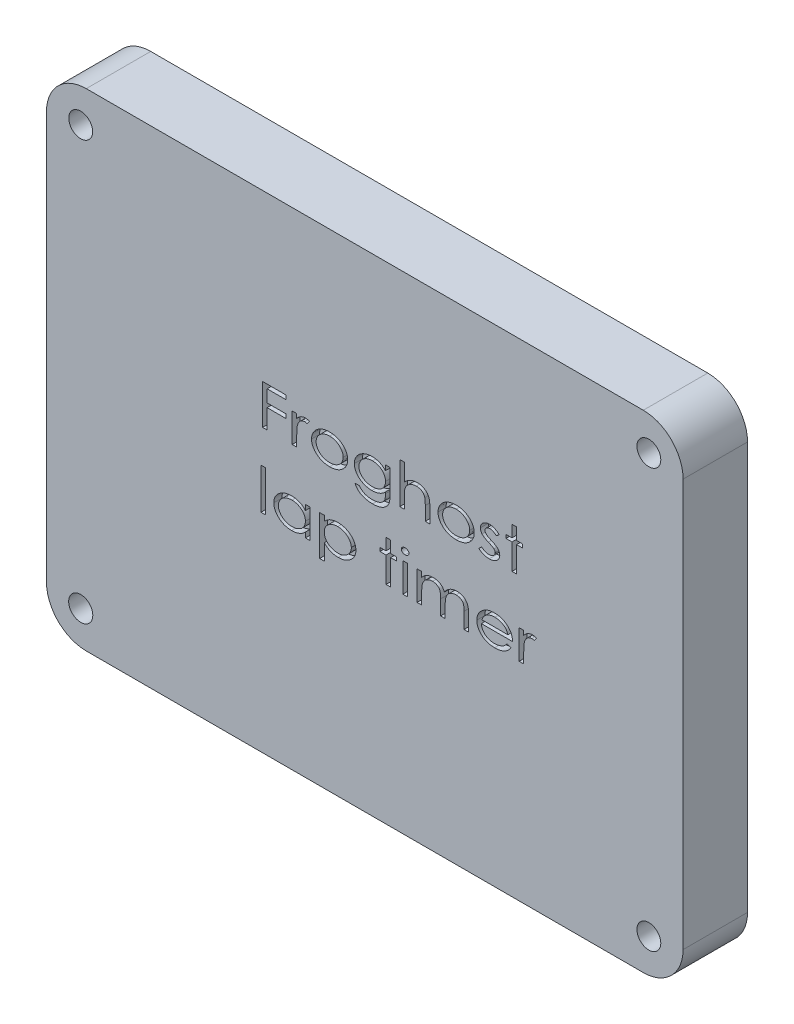
SolidWorks part; units mm, degrees
ref_plane "Plan de face" through (0, 0, 0) normal (0, 0, 1) x (1, 0, 0)
ref_plane "Plan de dessus" through (0, 0, 0) normal (0, 1, 0) x (1, 0, 0)
ref_plane "Plan de droite" through (0, 0, 0) normal (1, 0, 0) x (0, 0, -1)
sketch "Esquisse1" plane through (0, 0, 0) normal (0, 0, 1) x (1, 0, 0)
  line L0 (-22.7007, 21.2079) -> (44.6967, 21.2079)
  line L1 (-28.9007, 23.2079) -> (51.0993, 23.2079)
  line L2 (-28.9007, 23.2079) -> (-28.9007, -37.9921)
  line L3 (-28.9007, -37.9921) -> (51.0993, -37.9921)
  line L4 (51.0993, 23.2079) -> (51.0993, -37.9921)
  line L5 (49.0993, 17.0079) -> (49.0993, -31.7921)
  line L6 (44.8993, -35.9921) -> (-22.7007, -35.9921)
  line L7 (-26.9007, -31.7921) -> (-26.9007, 17.0079)
  arc A0 (-22.7007, 21.2079) -> (-26.9007, 17.0079) centre (-24.6007, 18.9079) cw
  arc A1 (-26.9007, -31.7921) -> (-22.7007, -35.9921) centre (-24.8007, -33.8921) cw
  arc A2 (44.6967, 21.2079) -> (49.0993, 17.0079) centre (46.898, 19.1079) ccw
  arc A3 (49.0993, -31.7921) -> (44.8993, -35.9921) centre (47.0205, -33.9133) ccw
  circle A4 centre (-24.6007, 18.9079) radius 1.5
  circle A6 centre (46.7993, 18.9079) radius 1.5
  circle A7 centre (46.7999, -33.6947) radius 1.4974
  circle A8 centre (-24.5961, -33.7076) radius 1.5162
extrude "Boss.-Extru.1" add sketch "Esquisse1" along normal blind 6.1
sketch "Esquisse2" plane through (0, 0, 6.1) normal (0, 0, 1) x (1, 0, 0)
  line L1 (-28.9007, 23.2079) -> (51.0993, 23.2079)
  line L2 (-28.9007, 23.2079) -> (-28.9007, -37.9921)
  line L3 (-28.9007, -37.9921) -> (51.0993, -37.9921)
  line L4 (51.0993, 23.2079) -> (51.0993, -37.9921)
extrude "Boss.-Extru.2" add sketch "Esquisse2" along normal blind 2
fillet "Congé1" radius 5 4 edges at (51.0993, 23.2079, 4.05) (51.0993, -37.9921, 4.05) (-28.9007, -37.9921, 4.05) (-28.9007, 23.2079, 4.05)
sketch "Esquisse3" plane through (0, 0, 0) normal (0, 0, -1) x (-1, 0, 0)
  circle A0 centre (-46.7993, 18.9079) radius 1.5
  circle A1 centre (24.6007, 18.9079) radius 1.5
  circle A2 centre (24.5961, -33.7076) radius 1.5162
  circle A3 centre (-46.7999, -33.6947) radius 1.4974
extrude "Enlèv. mat.-Extru.1" cut sketch "Esquisse3" against normal blind 18
sketch "Esquisse4" plane through (0, 0, 8.1) normal (0, 0, 1) x (1, 0, 0)
  text T0 "Froghost\r\nlap timer " font "Century Gothic" height 5
  point P1 (0, 0)
extrude "Enlèv. mat.-Extru.2" cut sketch "Esquisse4" against normal blind 1
